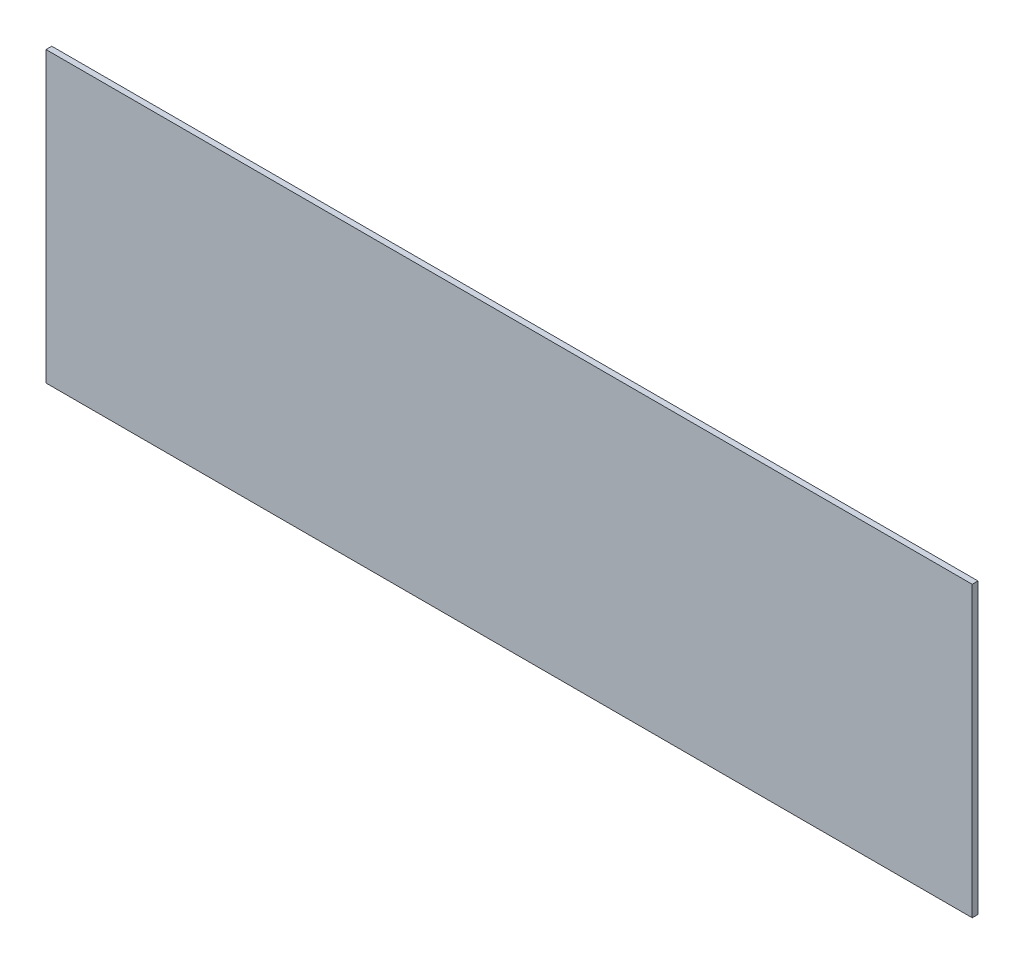
SolidWorks part; units mm, degrees
ref_plane "Спереди" through (0, 0, 0) normal (0, 0, 1) x (1, 0, 0)
ref_plane "Сверху" through (0, 0, 0) normal (0, 1, 0) x (1, 0, 0)
ref_plane "Справа" through (0, 0, 0) normal (1, 0, 0) x (0, 0, -1)
sketch "Эскиз1" plane through (0, 0, 0) normal (0, 0, 1) x (1, 0, 0)
  line L1 (-481, 150) -> (481, 150)
  line L2 (-481, 150) -> (-481, -150)
  line L3 (-481, -150) -> (481, -150)
  line L4 (481, 150) -> (481, -150)
  line L5 (-481, 150) -> (481, -150) construction
  line L6 (-481, -150) -> (481, 150) construction
  point P0 (0, 0)
  dimension "D1" = 300
  dimension "D2" = 962
extrude "Бобышка-Вытянуть1" add sketch "Эскиз1" along normal blind 6
